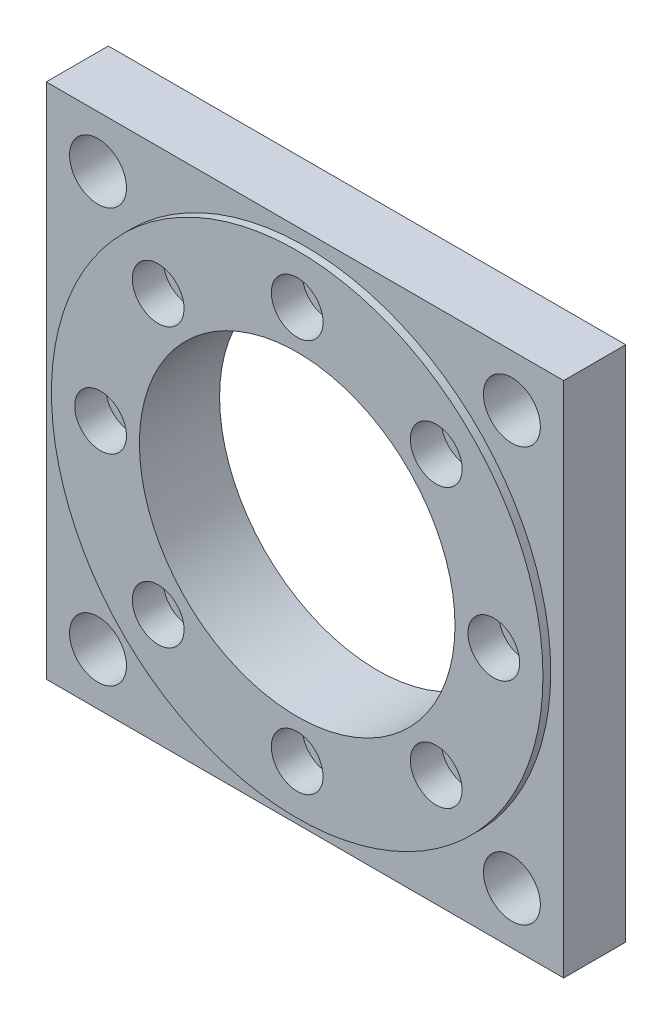
SolidWorks part; units mm, degrees
ref_plane "前视基准面" through (0, 0, 0) normal (0, 0, 1) x (1, 0, 0)
ref_plane "上视基准面" through (0, 0, 0) normal (0, 1, 0) x (1, 0, 0)
ref_plane "右视基准面" through (0, 0, 0) normal (1, 0, 0) x (0, 0, -1)
sketch "草图1" plane through (0, 0, 0) normal (0, 0, 1) x (1, 0, 0)
  circle A0 centre (0, 0) radius 34
  dimension "D1" = 68
extrude "拉伸1" add sketch "草图1" along normal blind 2
sketch "草图2" plane through (0, 0, 2) normal (0, 0, 1) x (1, 0, 0)
  line L1 (-50, 50) -> (50, 50)
  line L2 (-50, 50) -> (-50, -50)
  line L3 (-50, -50) -> (50, -50)
  line L4 (50, 50) -> (50, -50)
  circle A0 centre (0, 0) radius 34 construction
  dimension "D4" = 50
  dimension "D1" = 50
  dimension "D2" = 50
  dimension "D3" = 50
extrude "拉伸2" add sketch "草图2" along normal blind 12
sketch "草图3" plane through (0, 0, 0) normal (0, 0, -1) x (-1, 0, 0)
  circle A0 centre (0, 0) radius 30.5
  dimension "D1" = 61
extrude "切除-拉伸1" cut sketch "草图3" against normal through all
sketch "草图4" plane through (0, 0, 14) normal (0, 0, 1) x (1, 0, 0)
  circle A0 centre (26.8701, 26.8701) radius 3
  circle A1 centre (0, 38) radius 3
  circle A2 centre (38, 0) radius 3
  circle A3 centre (26.8701, -26.8701) radius 3
  circle A4 centre (0, -38) radius 3
  circle A5 centre (-26.8701, -26.8701) radius 3
  circle A6 centre (-38, 0) radius 3
  circle A7 centre (-26.8701, 26.8701) radius 3
extrude "切除-拉伸2" cut sketch "草图4" against normal through all
sketch "草图5" plane through (0, 0, 14) normal (0, 0, 1) x (1, 0, 0)
  circle A0 centre (0, 38) radius 5
  circle A1 centre (26.8701, 26.8701) radius 5
  circle A2 centre (38, 0) radius 5
  circle A3 centre (26.8701, -26.8701) radius 5
  circle A4 centre (0, -38) radius 5
  circle A5 centre (-26.8701, -26.8701) radius 5
  circle A6 centre (-38, 0) radius 5
  circle A7 centre (-26.8701, 26.8701) radius 5
  dimension "D1" = 10
extrude "切除-拉伸4" cut sketch "草图5" against normal blind 4.5
sketch "草图7" plane through (0, 0, 14) normal (0, 0, 1) x (1, 0, 0)
  circle A1 centre (-40, 40) radius 5.5
  circle A2 centre (40, 40) radius 5.5
  circle A3 centre (-40, -40) radius 5.5
  circle A4 centre (40, -40) radius 5.5
  dimension "D3" = 11
extrude "切除-拉伸6" cut sketch "草图7" against normal blind 50
sketch "草图8" plane through (0, 0, 14) normal (0, 0, 1) x (1, 0, 0)
  circle A0 centre (0, 0) radius 47.5
  circle A1 centre (26.8701, 26.8701) radius 5
  circle A2 centre (0, 38) radius 5
  circle A3 centre (38, 0) radius 5
  circle A4 centre (26.8701, -26.8701) radius 5
  circle A5 centre (0, -38) radius 5
  circle A6 centre (-26.8701, -26.8701) radius 5
  circle A7 centre (-38, 0) radius 5
  circle A8 centre (-26.8701, 26.8701) radius 5
  circle A11 centre (0, 0) radius 30.5
  dimension "D1" = 95
  dimension "D2" = 61
  dimension "D3" = 10
extrude "拉伸3" add sketch "草图8" along normal blind 1.5
